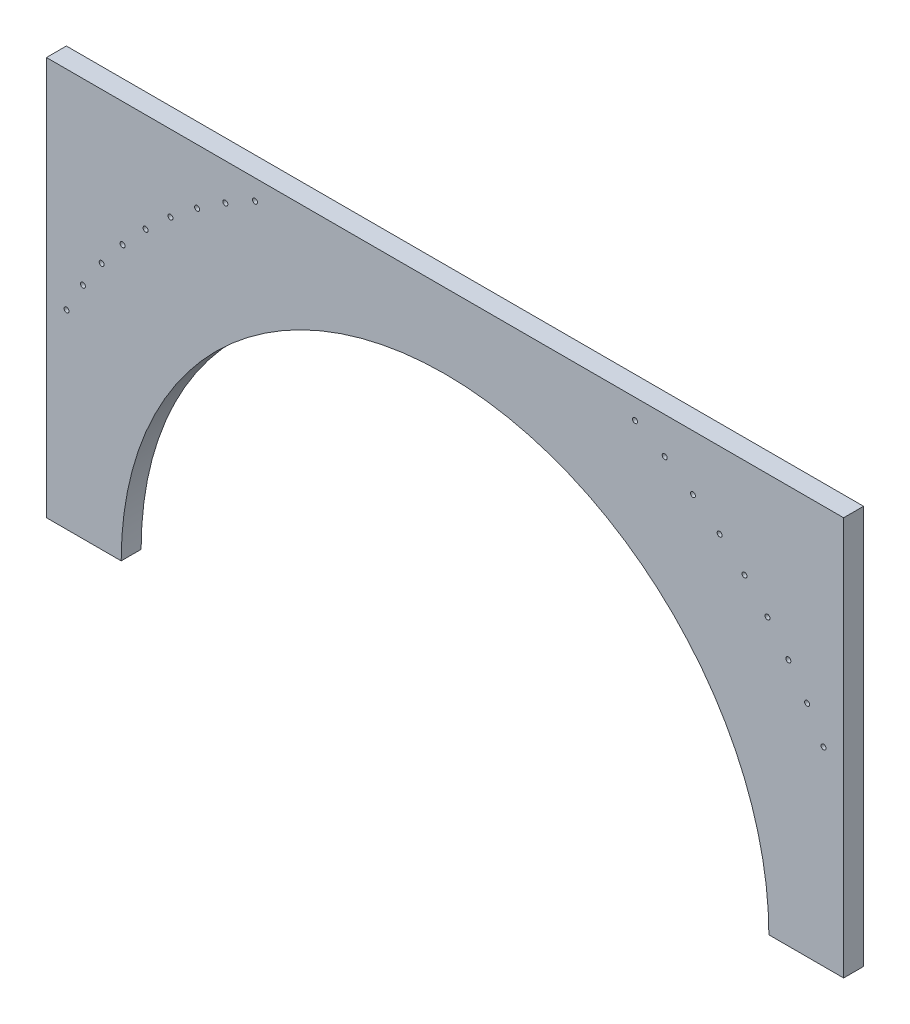
SolidWorks part; units mm, degrees
material "Epoxy, renforcé"
ref_plane "Plan de face" through (0, 0, 0) normal (0, 0, 1) x (1, 0, 0)
ref_plane "Plan de dessus" through (0, 0, 0) normal (0, 1, 0) x (1, 0, 0)
ref_plane "Plan de droite" through (0, 0, 0) normal (1, 0, 0) x (0, 0, -1)
sketch "Esquisse1" plane through (0, 0, 0) normal (0, 0, 1) x (1, 0, 0)
  line L0 (40, 0) -> (40, 40)
  line L1 (40, 40) -> (-40, 40)
  line L2 (-40, 40) -> (-40, 0)
  line L3 (40, 0) -> (32.5, 0)
  line L4 (-32.5, 0) -> (-40, 0)
  arc A0 (32.5, 0) -> (-32.5, 0) centre (0, 0) ccw
  dimension "D3" = 32.5
  dimension "D1" = 80
  dimension "D2" = 40
extrude "Boss.-Extru.1" add sketch "Esquisse1" along normal blind 2
sketch "Esquisse2" plane through (0, 0, 2) normal (0, 0, 1) x (1, 0, 0)
  line L0 (0, 40) -> (0, 0) construction
  line L1 (40, 40) -> (-40, 40) construction
  circle A0 centre (-37.9815, 19.0698) radius 0.25
  circle A1 centre (-36.3355, 22.0449) radius 0.25
  circle A2 centre (-34.4571, 24.8789) radius 0.25
  circle A3 centre (-32.3581, 27.5536) radius 0.25
  circle A4 centre (-30.052, 30.052) radius 0.25
  circle A5 centre (-27.5536, 32.3581) radius 0.25
  circle A6 centre (-24.8789, 34.4571) radius 0.25
  circle A7 centre (-22.0449, 36.3355) radius 0.25
  circle A8 centre (-19.0698, 37.9815) radius 0.25
  circle A9 centre (19.0698, 37.9815) radius 0.25
  circle A10 centre (22.0449, 36.3355) radius 0.25
  circle A11 centre (24.8789, 34.4571) radius 0.25
  circle A12 centre (27.5536, 32.3581) radius 0.25
  circle A13 centre (30.052, 30.052) radius 0.25
  circle A14 centre (32.3581, 27.5536) radius 0.25
  circle A15 centre (34.4571, 24.8789) radius 0.25
  circle A16 centre (36.3355, 22.0449) radius 0.25
  circle A17 centre (37.9815, 19.0698) radius 0.25
extrude "Enlèv. mat.-Extru.1" cut sketch "Esquisse2" against normal blind 2
